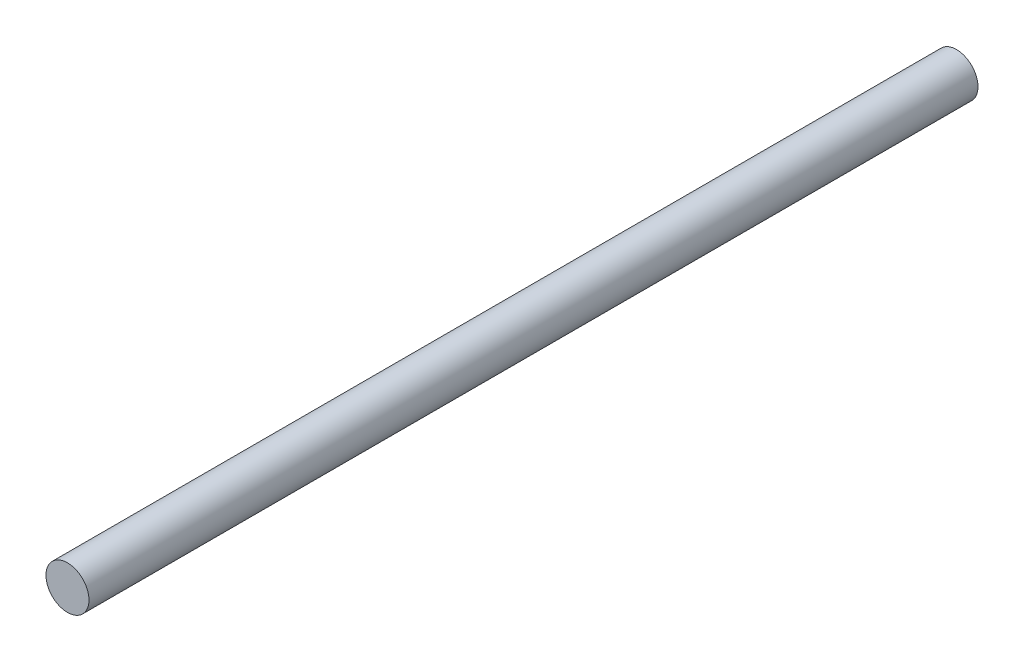
SolidWorks part; units mm, degrees
ref_plane "Plan de face" through (0, 0, 0) normal (0, 0, 1) x (1, 0, 0)
ref_plane "Plan de dessus" through (0, 0, 0) normal (0, 1, 0) x (1, 0, 0)
ref_plane "Plan de droite" through (0, 0, 0) normal (1, 0, 0) x (0, 0, -1)
sketch "Esquisse1" plane through (0, 0, 0) normal (0, 0, 1) x (1, 0, 0)
  circle A0 centre (0, 0) radius 1.5
  dimension "D1" = 3
extrude "Boss.-Extru.1" add sketch "Esquisse1" along normal blind 62
